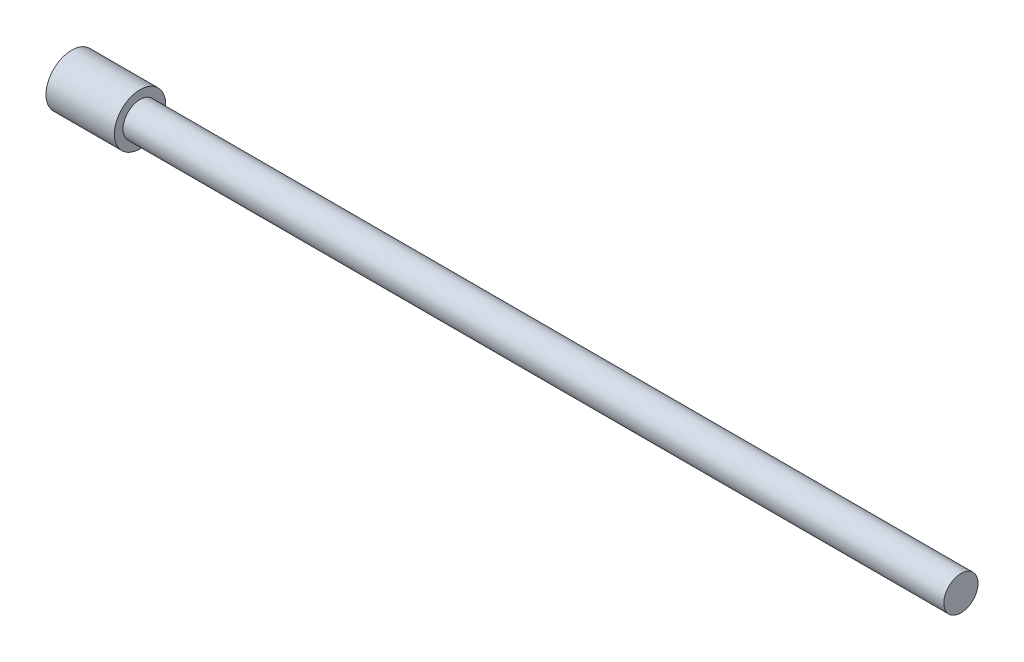
SolidWorks part; units mm, degrees
material "Galvanized Steel"
ref_plane "Front Plane" through (0, 0, 0) normal (0, 0, 1) x (1, 0, 0)
ref_plane "Top Plane" through (0, 0, 0) normal (0, 1, 0) x (1, 0, 0)
ref_plane "Right Plane" through (0, 0, 0) normal (1, 0, 0) x (0, 0, -1)
sketch "Sketch1" plane through (0, 0, 0) normal (1, 0, 0) x (0, 0, -1)
  circle A0 centre (0, 0) radius 6.35
  dimension "D1" = 12.7
extrude "Boss-Extrude1" add sketch "Sketch1" along normal mid plane 304.8
sketch "Sketch2" plane through (-152.4, 0, 0) normal (-1, 0, 0) x (0, 0, 1)
  circle A0 centre (0, 0) radius 9.525
  dimension "D1" = 19.05
extrude "Boss-Extrude2" add sketch "Sketch2" along normal blind 25.4
